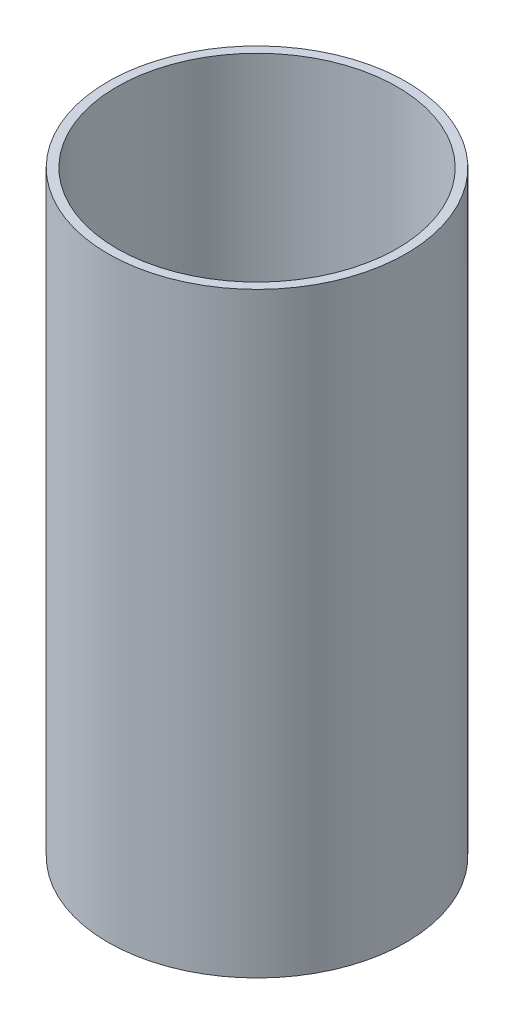
SolidWorks part; units mm, degrees
material "Plain Carbon Steel"
ref_plane "Front Plane" through (0, 0, 0) normal (0, 0, 1) x (1, 0, 0)
ref_plane "Top Plane" through (0, 0, 0) normal (0, 1, 0) x (1, 0, 0)
ref_plane "Right Plane" through (0, 0, 0) normal (1, 0, 0) x (0, 0, -1)
sketch "Sketch1" plane through (0, 0, 0) normal (0, 1, 0) x (1, 0, 0)
  circle A0 centre (0, 0) radius 50
  dimension "D1" = 100
extrude "Boss-Extrude1" add sketch "Sketch1" along normal blind 200
shell "Shell2" thickness 3
